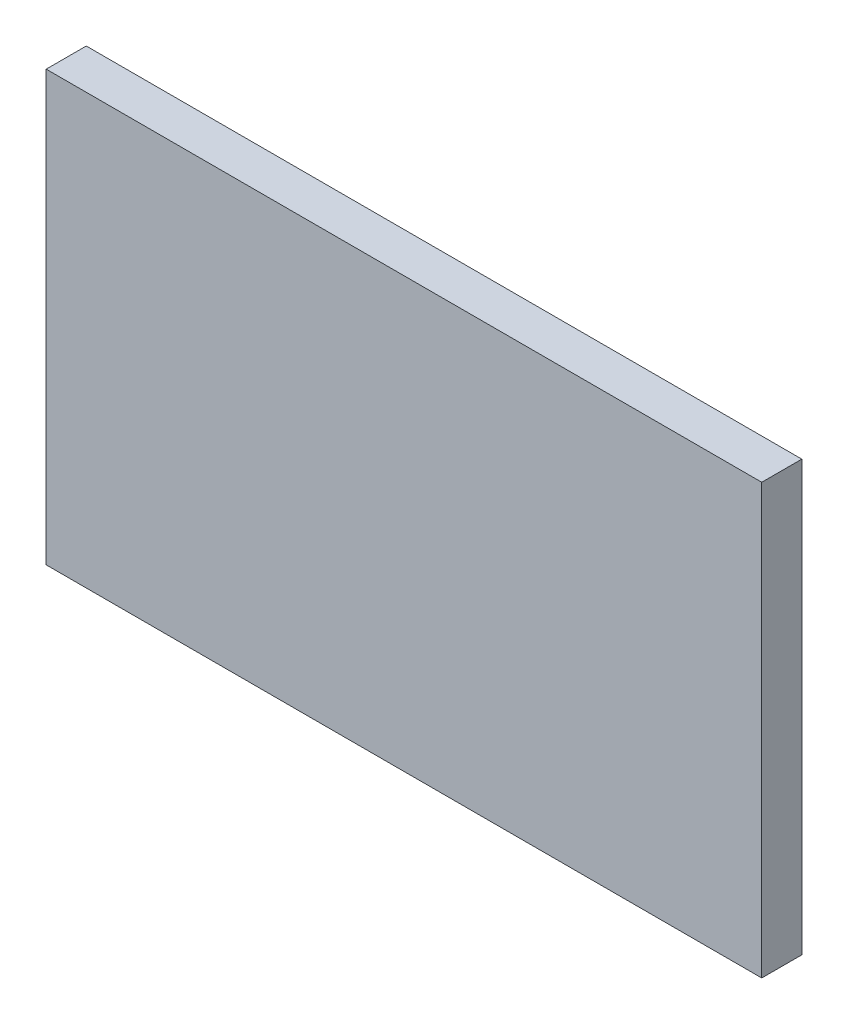
SolidWorks part; units mm, degrees
ref_plane "Alzado" through (0, 0, 0) normal (0, 0, 1) x (1, 0, 0)
ref_plane "Planta" through (0, 0, 0) normal (0, 1, 0) x (1, 0, 0)
ref_plane "Vista lateral" through (0, 0, 0) normal (1, 0, 0) x (0, 0, -1)
sketch "Croquis1" plane through (0, 0, 0) normal (0, 0, 1) x (1, 0, 0)
  line L1 (-79.1958, 25.3827) -> (-54.1958, 25.3827)
  line L2 (-79.1958, 25.3827) -> (-79.1958, 10.3827)
  line L3 (-79.1958, 10.3827) -> (-54.1958, 10.3827)
  line L4 (-54.1958, 25.3827) -> (-54.1958, 10.3827)
  dimension "D1" = 25
  dimension "D2" = 15
extrude "Saliente-Extruir1" add sketch "Croquis1" along normal blind 1.4
